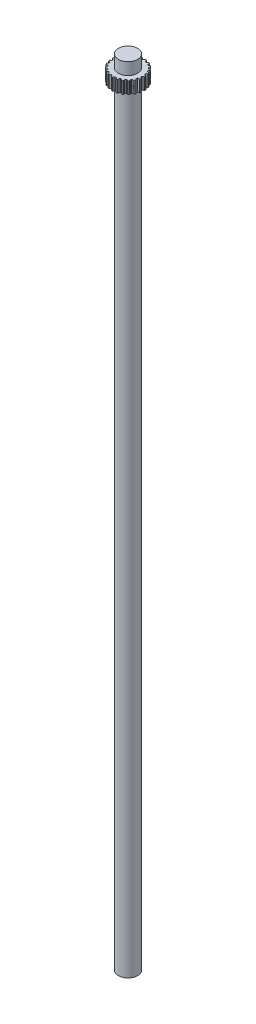
SolidWorks part; units mm, degrees
ref_plane "Front Plane" through (0, 0, 0) normal (0, 0, 1) x (1, 0, 0)
ref_plane "Top Plane" through (0, 0, 0) normal (0, 1, 0) x (1, 0, 0)
ref_plane "Right Plane" through (0, 0, 0) normal (1, 0, 0) x (0, 0, -1)
sketch "Sketch1" plane through (0, 0, 0) normal (0, 1, 0) x (1, 0, 0)
  circle A0 centre (0, 0) radius 4
  circle A1 centre (0, 0) radius 6
  dimension "D1" = 8
  dimension "D2" = 12
extrude "Boss-Extrude1" add sketch "Sketch1" along normal blind 5
sketch "Sketch2" plane through (0, 0, 0) normal (0, -1, 0) x (1, 0, 0)
  line L0 (0, 0) -> (0, 6.9454) construction
  line L1 (-0.35, 6.67) -> (0.35, 6.67)
  line L2 (-0.605, 5.9694) -> (-0.605, 5.6922)
  line L3 (-0.605, 5.6922) -> (0.6374, 5.6922)
  line L4 (0.6374, 5.6922) -> (0.605, 5.9694)
  circle A0 centre (0, 0) radius 6 construction
  spline S0 degree 2 poles (-0.605, 5.9694) (-0.3207, 6.2659) (-0.35, 6.67) knots 0 0 0 1 1 1
  spline S1 degree 2 poles (0.605, 5.9694) (0.3207, 6.2659) (0.35, 6.67) knots 0 0 0 1 1 1
  point P12 (-0.3891, 6.322)
  dimension "D1" = 6.67
  dimension "D2" = 0.7
  dimension "D3" = 1.21
extrude "Boss-Extrude2" add sketch "Sketch2" against normal up to surface (5 mm away) up to face at (0, 5, 6)
fillet "Fillet1" radius 0.1 2 edges at (-0.35, 2.5, 6.67) (0.35, 2.5, 6.67)
pattern_circular "CirPattern2" count 23 over 360 about axis through (0, 0, 0) along (0, 1, 0) of "Fillet1", "Boss-Extrude2"
sketch "Sketch3" plane through (0, 0, 0) normal (0, -1, 0) x (1, 0, 0)
  circle A0 centre (0, 0) radius 4 construction
  circle A1 centre (0, 0) radius 4
extrude "Boss-Extrude3" add sketch "Sketch3" along normal blind 320 and the other way blind 10
